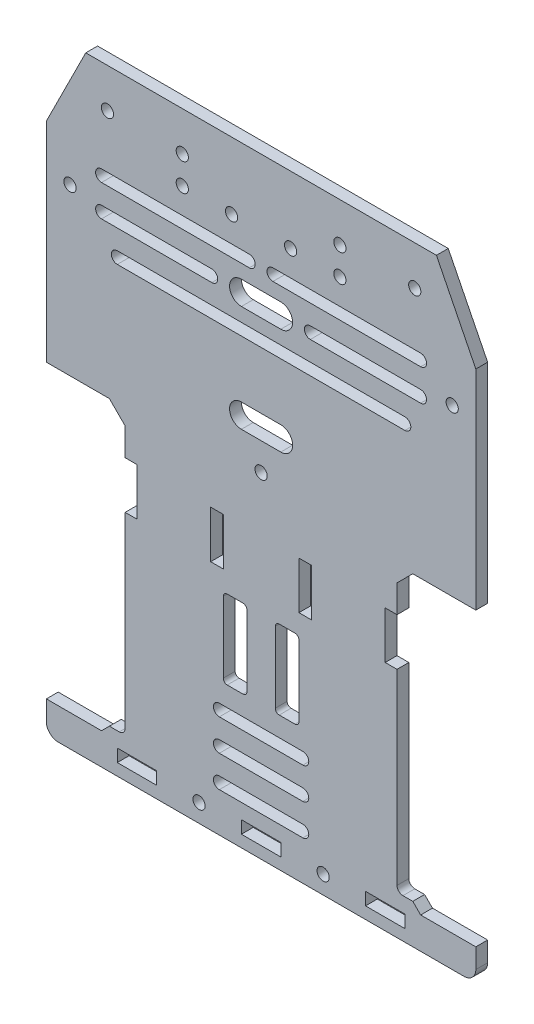
SolidWorks part; units mm, degrees
ref_plane "Plano frontal" through (0, 0, 0) normal (0, 0, 1) x (1, 0, 0)
ref_plane "Plano superior" through (0, 0, 0) normal (0, 1, 0) x (1, 0, 0)
ref_plane "Plano direito" through (0, 0, 0) normal (1, 0, 0) x (0, 0, -1)
sketch "Esboço1" plane through (0, 0, 0) normal (0, 0, 1) x (1, 0, 0)
  line L0 (0, 82) -> (16, 82)
  line L1 (3, 0) -> (106, 0)
  line L2 (0, 3) -> (0, 8)
  line L3 (10, 155) -> (99, 155)
  line L4 (109, 3) -> (109, 8)
  line L5 (16, 82) -> (20, 78)
  line L6 (20, 78) -> (20, 71)
  line L7 (20, 71) -> (23, 71)
  line L8 (23, 71) -> (23, 59)
  line L9 (23, 59) -> (20, 59)
  line L10 (20, 59) -> (20, 11.5)
  line L11 (59.1, 54) -> (63.1, 54)
  line L12 (18.5, 10) -> (16, 10)
  line L13 (109, 82) -> (93, 82)
  line L14 (93, 82) -> (89, 78)
  line L15 (89, 78) -> (89, 71)
  line L16 (89, 71) -> (86, 71)
  line L17 (86, 71) -> (86, 59)
  line L18 (86, 59) -> (89, 59)
  line L19 (89, 59) -> (89, 11.5)
  line L20 (41.7, 71) -> (44.9, 71)
  line L21 (90.5, 10) -> (93, 10)
  line L22 (109, 82) -> (109, 135)
  line L23 (0, 82) -> (0, 135)
  line L24 (41.7, 71) -> (41.7, 59)
  line L25 (41.7, 59) -> (44.9, 59)
  line L26 (44.9, 71) -> (44.9, 59)
  line L27 (67.3, 59) -> (64.1, 59)
  line L28 (67.3, 59) -> (67.3, 71)
  line L29 (67.3, 71) -> (64.1, 71)
  line L30 (64.1, 59) -> (64.1, 71)
  line L31 (45.9, 54) -> (49.9, 54)
  line L32 (44.9, 53) -> (44.9, 35)
  line L33 (45.9, 34) -> (49.9, 34)
  line L34 (50.9, 53) -> (50.9, 35)
  line L35 (93, 10) -> (95, 8)
  line L36 (95, 8) -> (109, 8)
  line L37 (16, 10) -> (14, 8)
  line L38 (14, 8) -> (0, 8)
  line L39 (58.1, 53) -> (58.1, 35)
  line L40 (64.1, 53) -> (64.1, 35)
  line L41 (59.1, 34) -> (63.1, 34)
  line L42 (109, 135) -> (99, 155)
  line L43 (0, 135) -> (10, 155)
  line L45 (91, 6.2) -> (81, 6.2)
  line L46 (91, 6.2) -> (91, 3)
  line L47 (91, 3) -> (81, 3)
  line L48 (81, 6.2) -> (81, 3)
  line L49 (59.5, 6.2) -> (49.5, 6.2)
  line L50 (59.5, 6.2) -> (59.5, 3)
  line L51 (59.5, 3) -> (49.5, 3)
  line L52 (49.5, 6.2) -> (49.5, 3)
  line L53 (18, 6.2) -> (28, 6.2)
  line L54 (18, 6.2) -> (18, 3)
  line L55 (18, 3) -> (28, 3)
  line L56 (28, 6.2) -> (28, 3)
  arc A0 (18.5, 10) -> (20, 11.5) centre (18.5, 11.5) ccw
  arc A1 (45.9, 54) -> (44.9, 53) centre (45.9, 53) ccw
  arc A2 (44.9, 35) -> (45.9, 34) centre (45.9, 35) ccw
  arc A3 (49.9, 34) -> (50.9, 35) centre (49.9, 35) ccw
  arc A4 (50.9, 53) -> (49.9, 54) centre (49.9, 53) ccw
  arc A5 (59.1, 54) -> (58.1, 53) centre (59.1, 53) ccw
  arc A6 (58.1, 35) -> (59.1, 34) centre (59.1, 35) ccw
  arc A7 (64.1, 53) -> (63.1, 54) centre (63.1, 53) ccw
  arc A8 (63.1, 34) -> (64.1, 35) centre (63.1, 35) ccw
  arc A9 (89, 11.5) -> (90.5, 10) centre (90.5, 11.5) ccw
  arc A10 (0, 3) -> (3, 0) centre (3, 3) ccw
  arc A11 (106, 0) -> (109, 3) centre (106, 3) ccw
  circle A12 centre (47, 138) radius 1.55
  circle A13 centre (62, 138) radius 1.55
  circle A14 centre (74.5, 138) radius 1.55
  circle A15 centre (34.5, 138) radius 1.55
  circle A16 centre (74.5, 145) radius 1.55
  circle A17 centre (93.5, 145) radius 1.55
  circle A18 centre (15.5, 145) radius 1.55
  circle A19 centre (34.5, 145) radius 1.55
  dimension "D2" = 16
  dimension "D15" = 3
  dimension "D23" = 1
  dimension "D24" = 6
  dimension "D26" = 1
  dimension "D30" = 3
  dimension "D31" = 45
  dimension "D37" = 6
  dimension "D40" = 3.1
  dimension "D1" = 20
  dimension "D3" = 20
  dimension "D4" = 16
  dimension "D5" = 45
  dimension "D6" = 3
  dimension "D7" = 7
  dimension "D8" = 12
  dimension "D9" = 3
  dimension "D10" = 72
  dimension "D11" = 45
  dimension "D12" = 7
  dimension "D13" = 12
  dimension "D14" = 72
  dimension "D16" = 10
  dimension "D17" = 109
  dimension "D18" = 3.2
  dimension "D19" = 12
  dimension "D20" = 18.7
  dimension "D21" = 18.7
  dimension "D22" = 73
  dimension "D25" = 20
  dimension "D27" = 6
  dimension "D28" = 20
  dimension "D29" = 5
  dimension "D32" = 45
  dimension "D33" = 14
  dimension "D34" = 14
  dimension "D35" = 2
  dimension "D36" = 2
  dimension "D38" = 3
  dimension "D39" = 3
  dimension "D41" = 12.5
  dimension "D42" = 40
  dimension "D43" = 12.5
  dimension "D44" = 17
  dimension "D45" = 34.5
  dimension "D46" = 19
  dimension "D47" = 19
  dimension "D48" = 10
  dimension "D49" = 10
  dimension "D50" = 10
  dimension "D51" = 20
  dimension "D52" = 20
  dimension "D53" = 3.2
  dimension "D54" = 3.2
  dimension "D55" = 3.2
  dimension "D56" = 10
  dimension "D57" = 10
  dimension "D58" = 10
  dimension "D59" = 3
  dimension "D60" = 18
  dimension "D61" = 18
  dimension "D62" = 21.5
extrude "Ressalto-extrusão1" add sketch "Esboço1" along normal blind 3
sketch "Esboço2" plane through (0, 0, 0) normal (0, 0, -1) x (-1, 0, 0)
  line L0 (-20, 59) -> (-20, 11.5) construction
  line L2 (-3, 0) -> (-106, 0) construction
  line L3 (-59.5, 3) -> (-59.5, 6.2) construction
  line L4 (-49.5, 6.2) -> (-49.5, 3) construction
  circle A0 centre (-54.5, 85) radius 1.55
  circle A1 centre (-70.25, 4.6) radius 1.55
  circle A2 centre (-38.75, 4.6) radius 1.55
  dimension "D1" = 3.1
  dimension "D2" = 34.5
  dimension "D3" = 85
  dimension "D4" = 4.6
  dimension "D5" = 10.75
  dimension "D6" = 10.75
extrude "Corte-extrusão1" cut sketch "Esboço2" against normal blind 10
sketch "Esboço3" plane through (0, 0, 3) normal (0, 0, 1) x (1, 0, 0)
  line L0 (109, 82) -> (109, 135) construction
  line L1 (93, 82) -> (109, 82) construction
  line L2 (0, 82) -> (16, 82) construction
  line L3 (0, 135) -> (0, 82) construction
  circle A0 centre (6, 124) radius 1.55
  circle A1 centre (103, 124) radius 1.55
  dimension "D1" = 3.1
  dimension "D2" = 6
  dimension "D3" = 42
  dimension "D4" = 42
  dimension "D5" = 6
extrude "Corte-extrusão2" cut sketch "Esboço3" against normal through all
sketch "Esboço5" plane through (0, 0, 0) normal (0, 0, -1) x (-1, 0, 0)
  line L0 (-95, 131.5) -> (-57.5, 131.5)
  line L1 (0, 135) -> (0, 82) construction
  line L2 (-57.5, 128.5) -> (-95, 128.5)
  line L3 (-51.5, 131.5) -> (-14, 131.5)
  line L4 (-109, 82) -> (-109, 135) construction
  line L5 (-14, 128.5) -> (-51.5, 128.5)
  line L6 (-109, 82) -> (-109, 135) construction
  line L7 (-99, 155) -> (-10, 155) construction
  line L8 (-59.5, 122) -> (-49.5, 122) construction
  line L9 (-59.5, 125) -> (-49.5, 125)
  line L10 (-59.5, 119) -> (-49.5, 119)
  line L11 (-95, 122) -> (-67, 122) construction
  line L12 (-95, 123.5) -> (-67, 123.5)
  line L13 (-95, 120.5) -> (-67, 120.5)
  line L14 (-42, 122) -> (-14, 122) construction
  line L15 (-42, 123.5) -> (-14, 123.5)
  line L16 (-42, 120.5) -> (-14, 120.5)
  line L17 (-91, 114) -> (-18, 114) construction
  line L18 (-91, 115.5) -> (-18, 115.5)
  line L19 (-91, 112.5) -> (-18, 112.5)
  line L20 (0, 135) -> (0, 82) construction
  line L21 (-59.5, 95) -> (-49.5, 95) construction
  line L22 (-59.5, 98) -> (-49.5, 98)
  line L23 (-59.5, 92) -> (-49.5, 92)
  line L24 (-65.1, 11.5) -> (-43.9, 11.5) construction
  line L25 (-65.1, 13) -> (-43.9, 13)
  line L26 (-65.1, 10) -> (-43.9, 10)
  line L27 (-44.9, 59) -> (-44.9, 71) construction
  line L28 (-64.1, 71) -> (-64.1, 59) construction
  line L29 (-3, 0) -> (-106, 0) construction
  line L30 (-65.1, 19.5) -> (-43.9, 19.5) construction
  line L31 (-65.1, 21) -> (-43.9, 21)
  line L32 (-65.1, 18) -> (-43.9, 18)
  line L33 (-65.1, 27.5) -> (-43.9, 27.5) construction
  line L34 (-65.1, 29) -> (-43.9, 29)
  line L35 (-65.1, 26) -> (-43.9, 26)
  arc A0 (-95, 131.5) -> (-95, 128.5) centre (-95, 130) ccw
  arc A1 (-57.5, 128.5) -> (-57.5, 131.5) centre (-57.5, 130) ccw
  arc A2 (-51.5, 131.5) -> (-51.5, 128.5) centre (-51.5, 130) ccw
  arc A3 (-14, 128.5) -> (-14, 131.5) centre (-14, 130) ccw
  arc A4 (-59.5, 125) -> (-59.5, 119) centre (-59.5, 122) ccw
  arc A5 (-49.5, 119) -> (-49.5, 125) centre (-49.5, 122) ccw
  arc A6 (-95, 123.5) -> (-95, 120.5) centre (-95, 122) ccw
  arc A7 (-67, 120.5) -> (-67, 123.5) centre (-67, 122) ccw
  arc A8 (-42, 123.5) -> (-42, 120.5) centre (-42, 122) ccw
  arc A9 (-14, 120.5) -> (-14, 123.5) centre (-14, 122) ccw
  arc A10 (-91, 115.5) -> (-91, 112.5) centre (-91, 114) ccw
  arc A11 (-18, 112.5) -> (-18, 115.5) centre (-18, 114) ccw
  arc A12 (-59.5, 98) -> (-59.5, 92) centre (-59.5, 95) ccw
  arc A13 (-49.5, 92) -> (-49.5, 98) centre (-49.5, 95) ccw
  circle A14 centre (-54.5, 85) radius 1.55 construction
  arc A15 (-65.1, 13) -> (-65.1, 10) centre (-65.1, 11.5) ccw
  arc A16 (-43.9, 10) -> (-43.9, 13) centre (-43.9, 11.5) ccw
  arc A17 (-65.1, 21) -> (-65.1, 18) centre (-65.1, 19.5) ccw
  arc A18 (-43.9, 18) -> (-43.9, 21) centre (-43.9, 19.5) ccw
  arc A19 (-65.1, 29) -> (-65.1, 26) centre (-65.1, 27.5) ccw
  arc A20 (-43.9, 26) -> (-43.9, 29) centre (-43.9, 27.5) ccw
  point P20 (-54.5, 122)
  point P27 (-81, 122)
  point P32 (-28, 122)
  point P41 (-54.5, 114)
  point P52 (-54.5, 95)
  point P61 (-54.5, 11.5)
  point P74 (-54.5, 19.5)
  point P81 (-54.5, 27.5)
  dimension "D1" = 1.5
  dimension "D2" = 1.5
  dimension "D3" = 1.5
  dimension "D4" = 1.5
  dimension "D11" = 3
  dimension "D13" = 1.5
  dimension "D14" = 1.5
  dimension "D19" = 1.5
  dimension "D24" = 10
  dimension "D25" = 5
  dimension "D29" = 1.5
  dimension "D5" = 6
  dimension "D6" = 14
  dimension "D7" = 14
  dimension "D8" = 7.5
  dimension "D9" = 25
  dimension "D10" = 10
  dimension "D12" = 8
  dimension "D15" = 28
  dimension "D16" = 28
  dimension "D17" = 14
  dimension "D18" = 14
  dimension "D20" = 73
  dimension "D21" = 18
  dimension "D22" = 8
  dimension "D23" = 10
  dimension "D26" = 6
  dimension "D27" = 1
  dimension "D28" = 1
  dimension "D30" = 11.5
  dimension "D31" = 8
  dimension "D32" = 8
extrude "Corte-extrusão5" cut sketch "Esboço5" against normal blind 10
